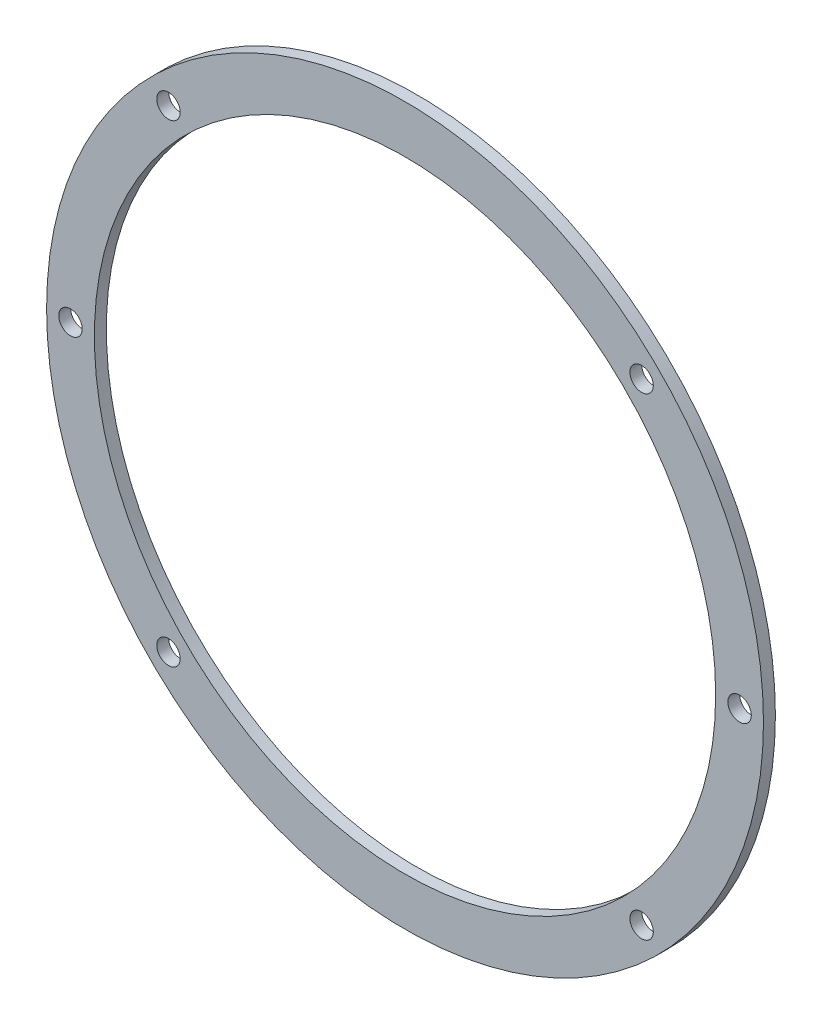
SolidWorks part; units mm, degrees
material "Hexcel AS4C (3000 Filaments)"
ref_plane "Front Plane" through (0, 0, 0) normal (0, 0, 1) x (1, 0, 0)
ref_plane "Top Plane" through (0, 0, 0) normal (0, 1, 0) x (1, 0, 0)
ref_plane "Right Plane" through (0, 0, 0) normal (1, 0, 0) x (0, 0, -1)
sketch "Sketch1" plane through (0, 0, 0) normal (0, 0, 1) x (1, 0, 0)
  circle A0 centre (0, 0) radius 76.2
  circle A1 centre (0, 0) radius 66.04
  dimension "D1" = 152.4
  dimension "D2" = 10.16
extrude "Boss-Extrude1" add sketch "Sketch1" along normal blind 2.54
hole_wizard "#10 Clearance Hole1" positions "Sketch3" profile "Sketch2" hole size "#10" standard "ANSI Inch"
sketch "Sketch3" plane through (0, 0, 2.54) normal (0, 0, 1) x (1, 0, 0)
  line L0 (-76.2, 0) -> (76.2, 0) construction
  line L1 (-53.8815, -53.8815) -> (53.8815, 53.8815) construction
  line L3 (-53.8815, 53.8815) -> (53.8815, -53.8815) construction
  circle A0 centre (0, 0) radius 76.2 construction
  circle A1 centre (0, 0) radius 71.12 construction
  point P17 (-50.2894, 50.2894)
  point P19 (-71.12, 0)
  point P21 (-50.2894, -50.2894)
  point P23 (50.2894, -50.2894)
  point P25 (71.12, 0)
  point P27 (50.2894, 50.2894)
  dimension "D3" = 142.24
  dimension "D1" = 45
  dimension "D2" = 45
sketch "Sketch2" plane through (-50.2894, 50.2894, 2.54) normal (1, 0, 0) x (0, -1, 0)
  line L0 (0, 0) -> (0, 39.8497)
  line L1 (0, 39.8497) -> (2.4892, 38.354)
  line L2 (2.4892, 38.354) -> (2.4892, 0)
  line L5 (2.4892, 0) -> (0, 0)
  line L10 (0, 39.8497) -> (-2.4892, 38.354) construction
  line L11 (0, -6.35) -> (0, 107.95) construction
  dimension "Hole Dia." = 4.9784
  dimension "Hole Depth" = 38.354
  dimension "Drill Angle" = 118
